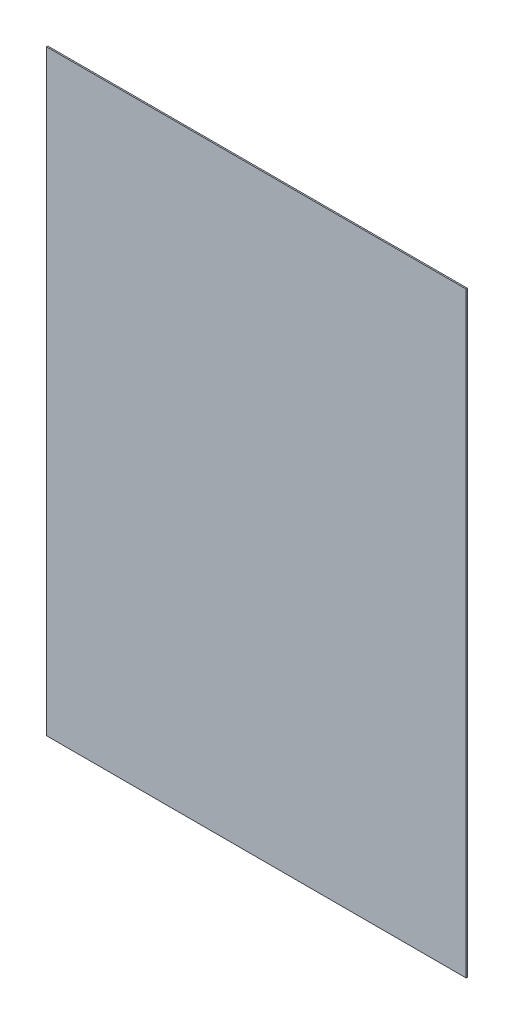
SolidWorks part; units mm, degrees
ref_plane "Alzado" through (0, 0, 0) normal (0, 0, 1) x (1, 0, 0)
ref_plane "Planta" through (0, 0, 0) normal (0, 1, 0) x (1, 0, 0)
ref_plane "Vista lateral" through (0, 0, 0) normal (1, 0, 0) x (0, 0, -1)
sketch "Croquis1" plane through (0, 0, 0) normal (0, 0, 1) x (1, 0, 0)
  line L1 (0, 0) -> (914.3, 0)
  line L2 (0, 0) -> (0, -1300)
  line L3 (0, -1300) -> (914.3, -1300)
  line L4 (914.3, 0) -> (914.3, -1300)
  dimension "D1" = 1300
  dimension "D2" = 914.3
extrude "Saliente-Extruir1" add sketch "Croquis1" along normal blind 2.9
